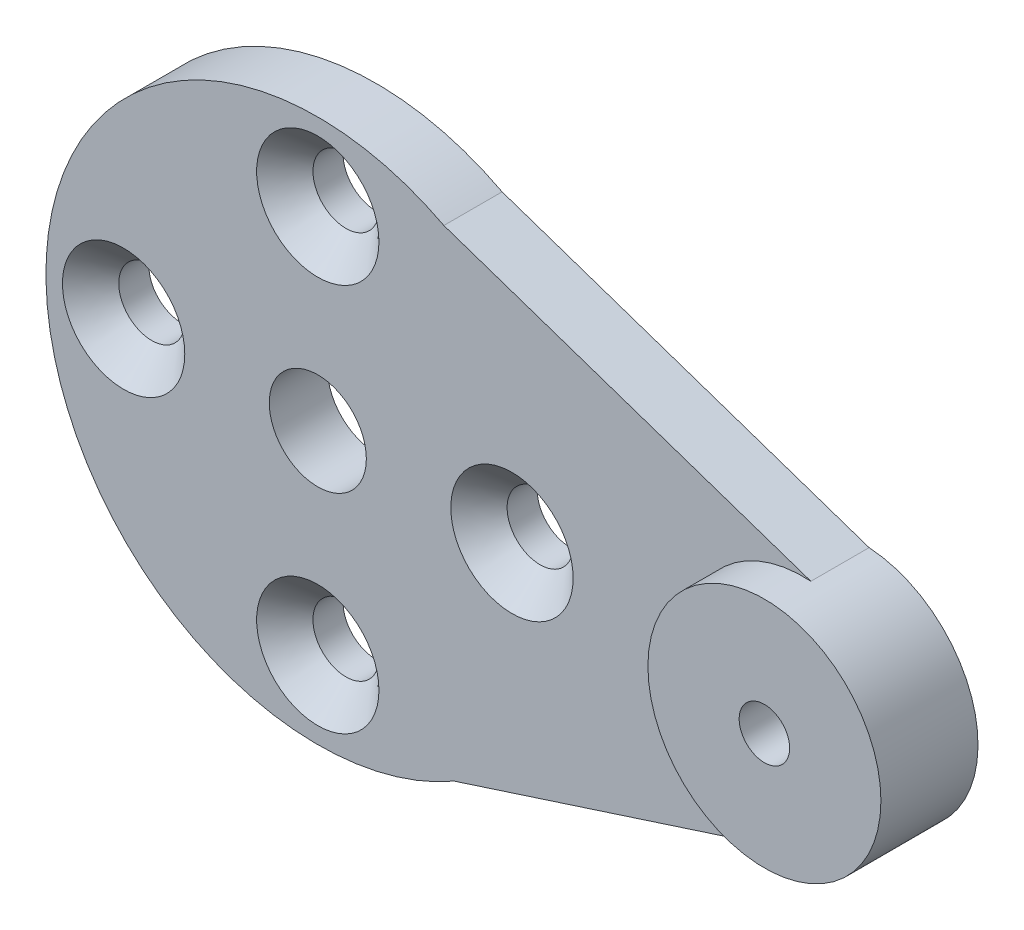
SolidWorks part; units mm, degrees
ref_plane "Front Plane" through (0, 0, 0) normal (0, 0, 1) x (1, 0, 0)
ref_plane "Top Plane" through (0, 0, 0) normal (0, 1, 0) x (1, 0, 0)
ref_plane "Right Plane" through (0, 0, 0) normal (1, 0, 0) x (0, 0, -1)
sketch "Sketch1" plane through (0, 0, 0) normal (0, 0, 1) x (1, 0, 0)
  line L1 (6.4921, 12.4037) -> (25.3934, 5.9871)
  line L2 (7.0229, -12.1111) -> (26.5781, -5.7887)
  arc A0 (6.4921, 12.4037) -> (7.0229, -12.1111) centre (0, 0) ccw
  arc A1 (26.5781, -5.7887) -> (25.3934, 5.9871) centre (25, 0) ccw
  dimension "D1" = 12
  dimension "D2" = 28
  dimension "D3" = 25
extrude "Boss-Extrude1" add sketch "Sketch1" along normal blind 3
sketch "Sketch2" plane through (0, 0, 3) normal (0, 0, 1) x (1, 0, 0)
  circle A0 centre (25, 0) radius 6
extrude "Boss-Extrude2" add sketch "Sketch2" along normal blind 2
sketch "Sketch3" plane through (0, 0, 5) normal (0, 0, 1) x (1, 0, 0)
  point P0 (25, 0)
hole_wizard "Tap Drill for M3x0.5 Tap1" positions "Sketch3" profile "Sketch4" hole size "M3x0.5" standard "JIS" end condition through all
sketch "Sketch4" plane through (25, 0, 5) normal (1, 0, 0) x (0, -1, 0)
  line L0 (0, 0) -> (0, 5)
  line L1 (0, 5) -> (1.3, 5)
  line L2 (1.3, 5) -> (1.3, 0)
  line L5 (1.3, 0) -> (0, 0)
  line L11 (0, -6.35) -> (0, 107.95) construction
  dimension "Thru Hole Dia." = 2.6
  dimension "Thru Hole Depth" = 5
sketch "Sketch5" plane through (0, 0, 3) normal (0, 0, 1) x (1, 0, 0)
  circle A0 centre (0, 0) radius 2.5
extrude "Cut-Extrude1" cut sketch "Sketch5" against normal through all
sketch "Sketch6" plane through (0, 0, 3) normal (0, 0, 1) x (1, 0, 0)
  point P0 (0, 10)
  point P2 (-10, 0)
  point P4 (0, -10)
  point P6 (10, 0)
hole_wizard "CSK for M3 Flat Countersunk Head Screw1" positions "Sketch6" profile "Sketch7" countersink size "M3" standard "JIS"
sketch "Sketch7" plane through (0, 10, 3) normal (1, 0, 0) x (0, -1, 0)
  line L0 (0, 0) -> (0, 7.0215)
  line L1 (0, 7.0215) -> (1.7, 6)
  line L2 (1.7, 6) -> (1.7, 1.45)
  line L3 (1.7, 1.45) -> (3.15, 0)
  line L5 (3.15, 0) -> (0, 0)
  line L6 (-1.7, 1.45) -> (-3.15, 0) construction
  line L10 (0, 7.0215) -> (-1.7, 6) construction
  line L11 (0, -6.35) -> (0, 107.95) construction
  dimension "Hole Dia." = 3.4
  dimension "Hole Depth" = 6
  dimension "Near C'Sink Dia." = 6.3
  dimension "Near C'Sink Angle" = 90
  dimension "Drill Angle" = 118
